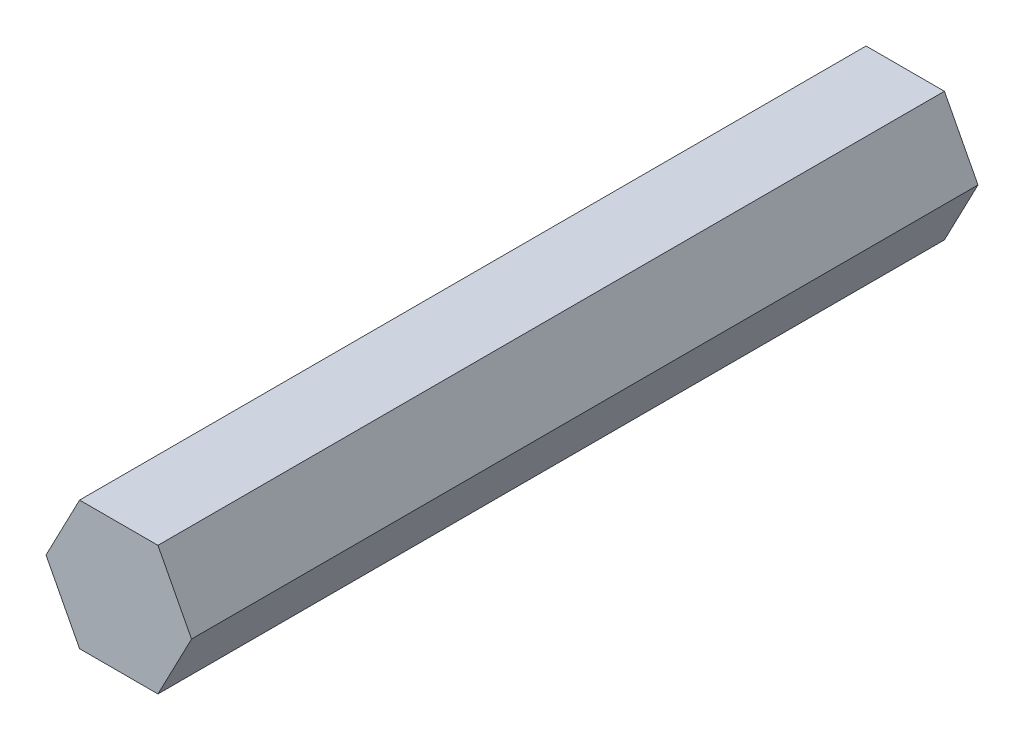
SolidWorks part; units mm, degrees
ref_plane "Alzado" through (0, 0, 0) normal (0, 0, 1) x (1, 0, 0)
ref_plane "Planta" through (0, 0, 0) normal (0, 1, 0) x (1, 0, 0)
ref_plane "Vista lateral" through (0, 0, 0) normal (1, 0, 0) x (0, 0, -1)
sketch "Sketch1" plane through (0, 0, 0) normal (0, 0, 1) x (1, 0, 0)
  line L0 (-1.4, 4.6) -> (1.4, 4.6)
  line L1 (-1.4, 0) -> (1.4, 0)
  line L2 (-2.6, 2.3) -> (6.18, 2.3) construction
  line L3 (-1.4, 0) -> (-2.5998, 2.3)
  line L4 (-2.5998, 2.3) -> (-1.4, 4.6)
  line L5 (1.4, 0) -> (2.5998, 2.3)
  line L6 (2.5998, 2.3) -> (1.4, 4.6)
  line L7 (0, 0) -> (0, 4.6041) construction
  point P7 (-4.6434, 2.3)
  point P10 (-4.0499, 2.3)
  point P11 (-2.6576, 2.3)
  point P12 (-3.5478, 2.3)
  point P15 (0, 0)
  point P16 (-3.1033, 2.3)
  point P17 (3.1033, 2.3)
  point P18 (-3.2483, 2.3)
  point P19 (3.2483, 2.3)
  point P20 (-3.2483, 2.3)
  point P21 (0, 0)
  point P22 (0, 0)
  dimension "D1" = 4.6
  dimension "D2" = 2.8
  dimension "D3" = 2.8
  dimension "D4" = 2.3
  dimension "D5" = 2.6
extrude "Boss-Extrude1" add sketch "Sketch1" along normal blind 28.1
sketch "Sketch2" plane through (0, 0, 0) normal (0, 0, -1) x (-1, 0, 0)
  line L0 (2.5998, 2.3) -> (-2.5998, 2.3) construction
  circle A0 centre (0, 2.3) radius 1.5
  dimension "D1" = 3
extrude "Cut-Extrude1" cut sketch "Sketch2" against normal blind 2
